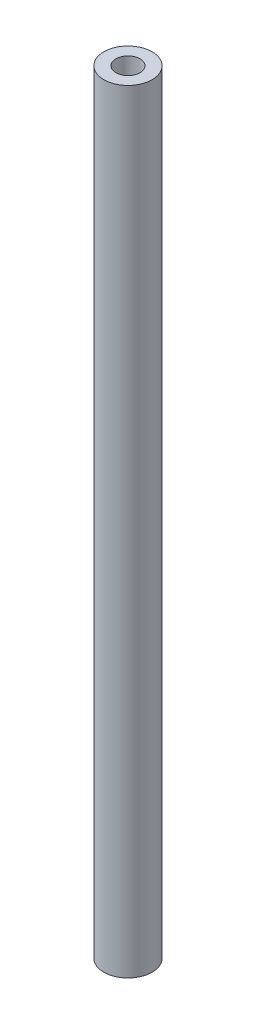
SolidWorks part; units mm, degrees
ref_plane "Front Plane" through (0, 0, 0) normal (0, 0, 1) x (1, 0, 0)
ref_plane "Top Plane" through (0, 0, 0) normal (0, 1, 0) x (1, 0, 0)
ref_plane "Right Plane" through (0, 0, 0) normal (1, 0, 0) x (0, 0, -1)
sketch "Sketch1" plane through (0, 0, 0) normal (0, 1, 0) x (1, 0, 0)
  circle A0 centre (0, 0) radius 6.35
  circle A1 centre (0, 0) radius 3.175
  dimension "D1" = 12.7
  dimension "D2" = 3.175
extrude "Boss-Extrude1" add sketch "Sketch1" along normal blind 203.2
equation "\"Pstrut_L\"= 36in"
equation "\"Pstrut_D\"= 1in"
equation "\"Pstrut_T\"= 0.25"
equation "\"Sstrut_L\"= 36in"
equation "\"Sstrut_D\"= 0.5in"
equation "\"Sstrut_T\"= 0.125"
equation "\"Dstrut_L\"= 10in"
equation "\"Dstrut_D\"= 0.5in"
equation "\"Dstrut_T\"= 0.125"
equation "\"D1@Sketch1\"=\"Dstrut_D\""
equation "\"D2@Sketch1\"=\"Dstrut_T\""
equation "\"D1@Boss-Extrude1\"=\"Dstrut_L\"-2"
